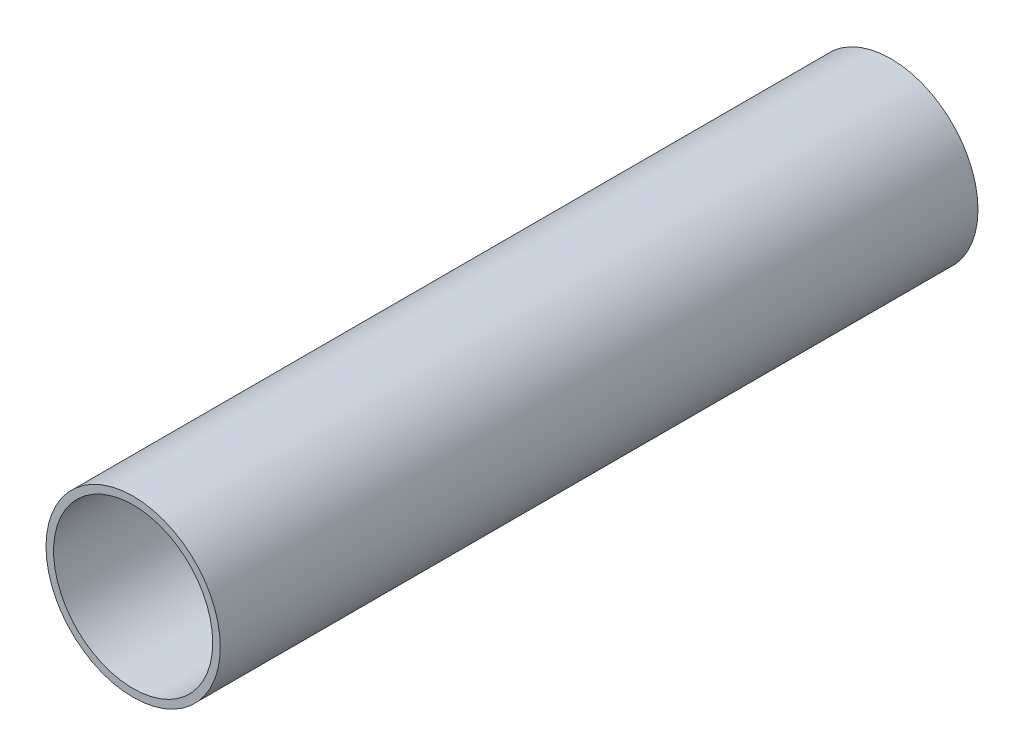
SolidWorks part; units mm, degrees
ref_plane "Plan de face" through (0, 0, 0) normal (0, 0, 1) x (1, 0, 0)
ref_plane "Plan de dessus" through (0, 0, 0) normal (0, 1, 0) x (1, 0, 0)
ref_plane "Plan de droite" through (0, 0, 0) normal (1, 0, 0) x (0, 0, -1)
sketch "Esquisse1" plane through (0, 0, 0) normal (0, 0, 1) x (1, 0, 0)
  circle A0 centre (0, 0) radius 10.5
  circle A1 centre (0, 0) radius 11.5
  dimension "D1" = 21
  dimension "D2" = 23
extrude "Boss.-Extru.1" add sketch "Esquisse1" along normal blind 100
